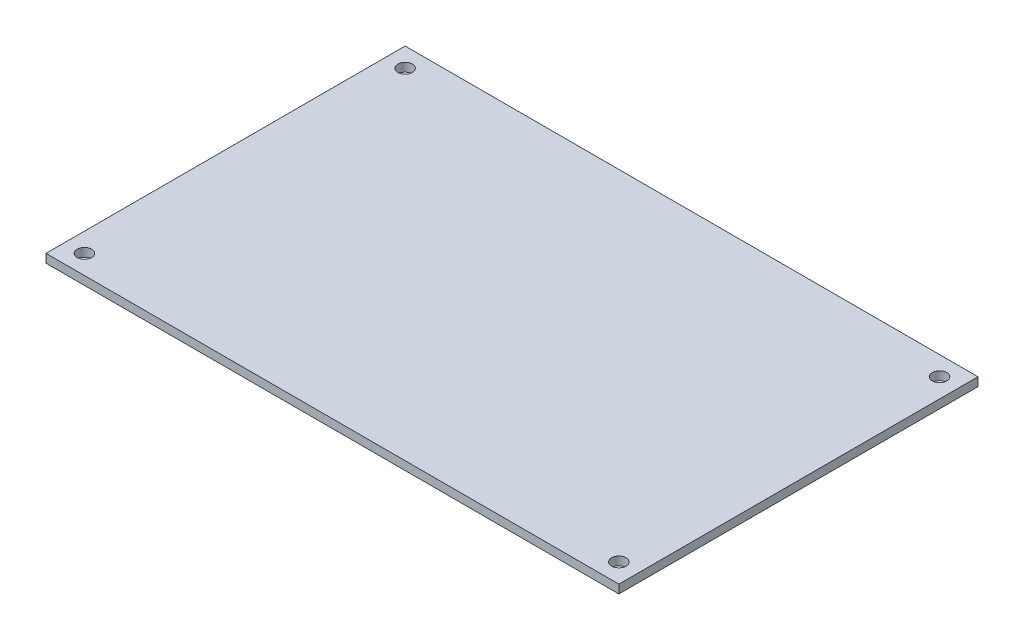
SolidWorks part; units mm, degrees
material "Thornel Mat VMA"
ref_plane "Front Plane" through (0, 0, 0) normal (0, 0, 1) x (1, 0, 0)
ref_plane "Top Plane" through (0, 0, 0) normal (0, 1, 0) x (1, 0, 0)
ref_plane "Right Plane" through (0, 0, 0) normal (1, 0, 0) x (0, 0, -1)
sketch "Sketch1" plane through (0, 0, 0) normal (0, 1, 0) x (1, 0, 0)
  line L1 (0, 0) -> (134, 0)
  line L2 (0, 0) -> (0, 84)
  line L3 (0, 84) -> (134, 84)
  line L4 (134, 0) -> (134, 84)
  dimension "D1" = 134
  dimension "D2" = 84
extrude "Boss-Extrude1" add sketch "Sketch1" along normal blind 2
sketch "Sketch2" plane through (0, 2, 0) normal (0, 1, 0) x (1, 0, 0)
  line L0 (67, 42) -> (67, 84) construction
  line L2 (134, 84) -> (0, 84) construction
  line L3 (129.5, 79.5) -> (4.5, 79.5) construction
  line L4 (129.5, 79.5) -> (129.5, 4.5) construction
  line L5 (129.5, 4.5) -> (4.5, 4.5) construction
  line L6 (4.5, 79.5) -> (4.5, 4.5) construction
  line L7 (129.5, 79.5) -> (4.5, 4.5) construction
  line L8 (129.5, 4.5) -> (4.5, 79.5) construction
  line L11 (0, 0) -> (134, 0) construction
  line L13 (134, 0) -> (134, 84) construction
  line L14 (67, 42) -> (134, 42) construction
  line L15 (67, 42) -> (0, 42) construction
  line L16 (0, 84) -> (0, 0) construction
  line L17 (67, 42) -> (67, 0) construction
  circle A0 centre (4.5, 4.5) radius 1.6
  circle A1 centre (4.5, 79.5) radius 1.6
  circle A2 centre (129.5, 79.5) radius 1.6
  circle A3 centre (129.5, 4.5) radius 1.6
  point P8 (67, 42)
  dimension "D1" = 3.2
  dimension "D2" = 125
  dimension "D3" = 75
hole_wizard "M3 Clearance Hole1" positions "Sketch4" profile "Sketch3" hole size "M3" standard "ANSI Metric"
sketch "Sketch4" plane through (0, 2, 0) normal (0, 1, 0) x (1, 0, 0)
  point P0 (4.5, 79.5)
  point P3 (129.5, 79.5)
  point P6 (129.5, 4.5)
  point P9 (4.5, 4.5)
sketch "Sketch3" plane through (4.5, 2, -79.5) normal (1, 0, 0) x (0, 0, 1)
  line L0 (0, 0) -> (0, 6.0215)
  line L1 (0, 6.0215) -> (1.7, 5)
  line L2 (1.7, 5) -> (1.7, 0)
  line L5 (1.7, 0) -> (0, 0)
  line L10 (0, 6.0215) -> (-1.7, 5) construction
  line L11 (0, -6.35) -> (0, 107.95) construction
  dimension "Hole Dia." = 3.4
  dimension "Hole Depth" = 5
  dimension "Drill Angle" = 118
